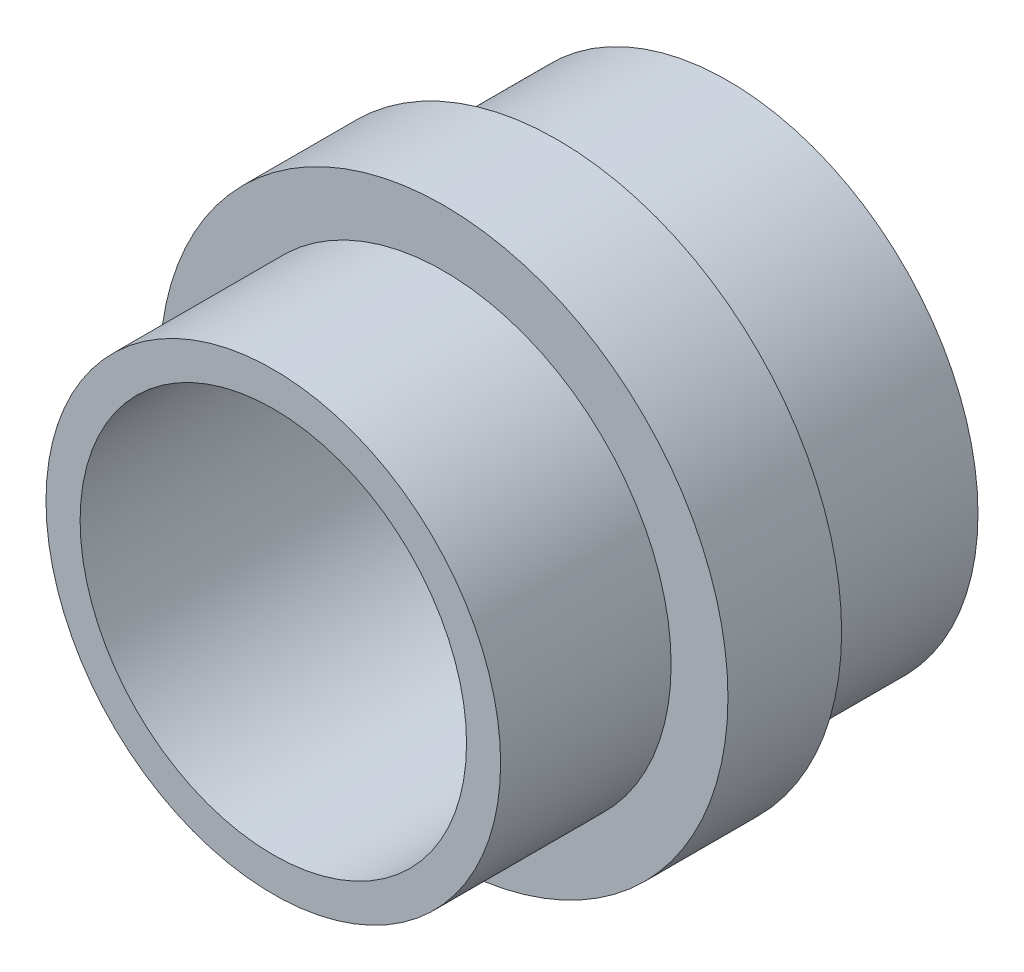
SolidWorks part; units mm, degrees
material "СТ3КП"
ref_plane "Спереди" through (0, 0, 0) normal (0, 0, 1) x (1, 0, 0)
ref_plane "Сверху" through (0, 0, 0) normal (0, 1, 0) x (1, 0, 0)
ref_plane "Справа" through (0, 0, 0) normal (1, 0, 0) x (0, 0, -1)
sketch "Эскиз1" plane through (0, 0, 0) normal (1, 0, 0) x (0, 0, -1)
  line L0 (-1506.993, 0) -> (73842.6562, 0) construction
  line L1 (-15, 17) -> (25, 17)
  line L2 (25, 17) -> (25, 22)
  line L3 (25, 22) -> (10, 22)
  line L4 (10, 22) -> (10, 25)
  line L5 (10, 25) -> (0, 25)
  line L6 (0, 25) -> (0, 20)
  line L7 (0, 20) -> (-15, 20)
  line L8 (-15, 20) -> (-15, 17)
  dimension "D1" = 34
  dimension "D2" = 50
  dimension "D3" = 40
  dimension "D4" = 44
  dimension "D5" = 15
  dimension "D6" = 10
  dimension "D7" = 15
revolve "Повернуть1" add sketch "Эскиз1" angle 360 about L0
